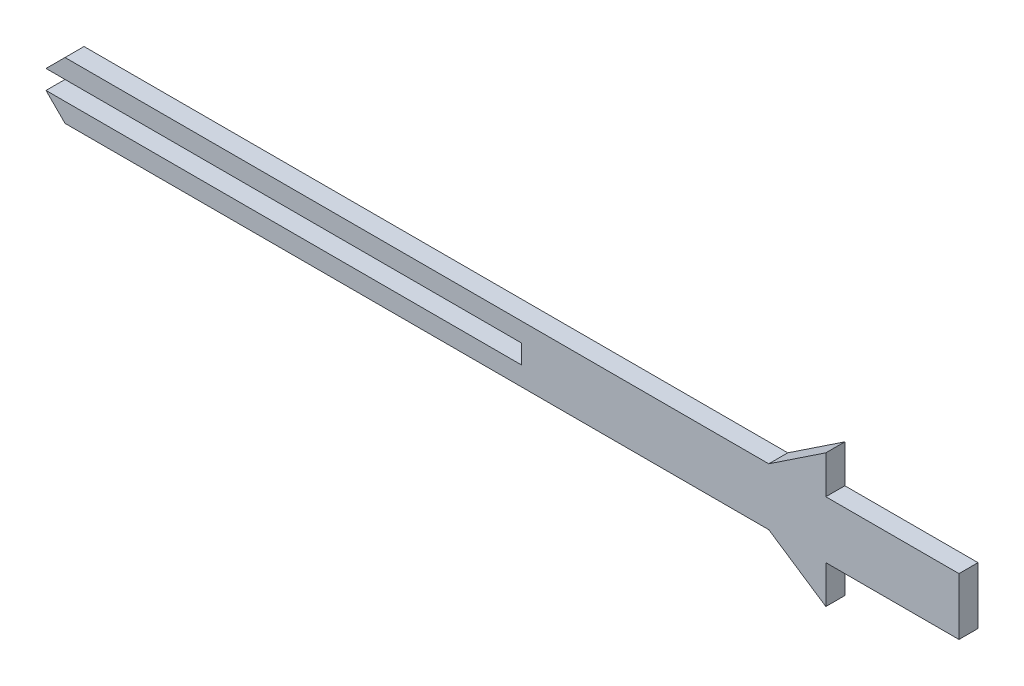
SolidWorks part; units mm, degrees
ref_plane "Front Plane" through (0, 0, 0) normal (0, 0, 1) x (1, 0, 0)
ref_plane "Top Plane" through (0, 0, 0) normal (0, 1, 0) x (1, 0, 0)
ref_plane "Right Plane" through (0, 0, 0) normal (1, 0, 0) x (0, 0, -1)
sketch "Sketch1" plane through (0, 0, 0) normal (0, 0, 1) x (1, 0, 0)
  line L963 (421.2925, 15.0172) -> (421.2925, 12.0172)
  line L964 (421.2925, 12.0172) -> (346.2925, 12.0172)
  line L965 (346.2925, 12.0172) -> (349.2925, 9.0172)
  line L966 (349.2925, 9.0172) -> (460.2925, 9.0172)
  line L967 (460.2925, 9.0172) -> (469.2925, 3.0172)
  line L968 (469.2925, 3.0172) -> (469.2925, 9.0172)
  line L969 (469.2925, 9.0172) -> (490.2925, 9.0172)
  line L970 (490.2925, 9.0172) -> (490.2925, 18.0172)
  line L971 (490.2925, 18.0172) -> (469.2925, 18.0172)
  line L972 (469.2925, 18.0172) -> (469.2925, 24.0172)
  line L973 (469.2925, 24.0172) -> (460.2925, 18.0172)
  line L974 (460.2925, 18.0172) -> (349.2925, 18.0172)
  line L975 (349.2925, 18.0172) -> (346.2925, 15.0172)
  line L976 (346.2925, 15.0172) -> (421.2925, 15.0172)
extrude "Boss-Extrude1" add sketch "Sketch1" along normal blind 3
